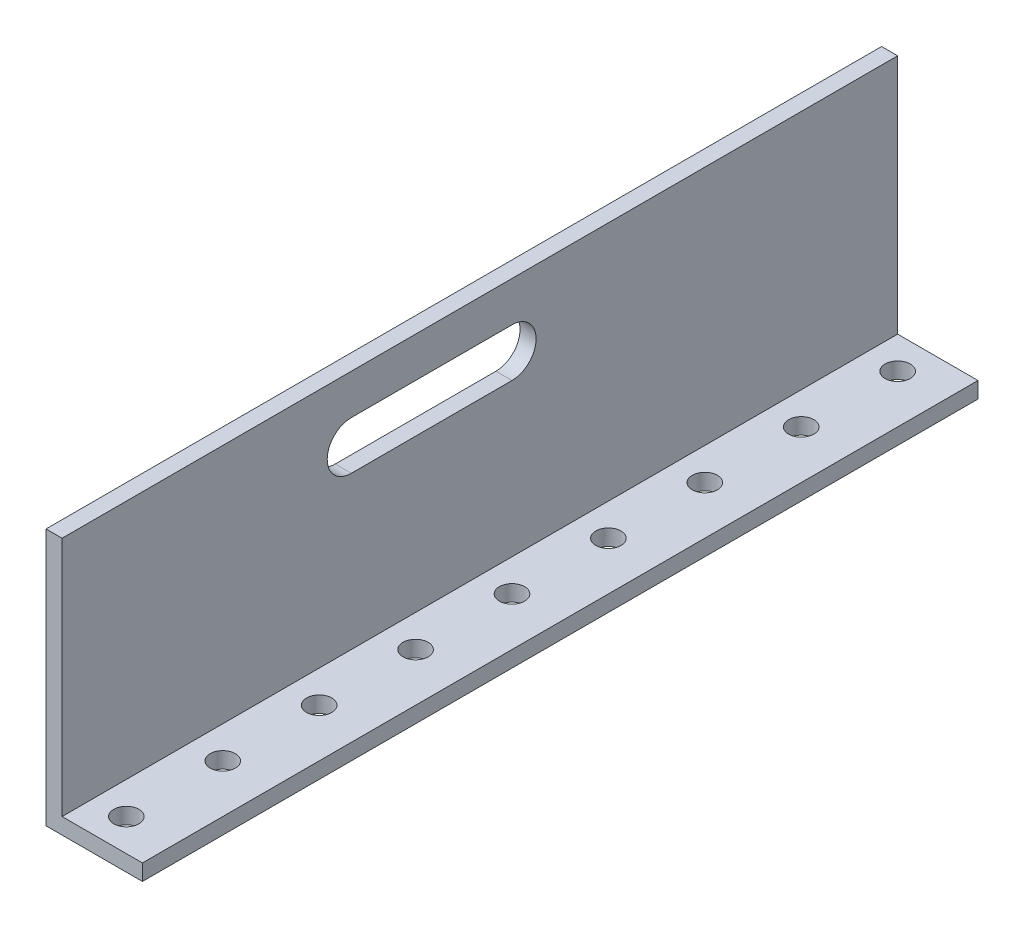
SolidWorks part; units mm, degrees
material "6061-T6 (SS)"
ref_plane "Front Plane" through (0, 0, 0) normal (0, 0, 1) x (1, 0, 0)
ref_plane "Top Plane" through (0, 0, 0) normal (0, 1, 0) x (1, 0, 0)
ref_plane "Right Plane" through (0, 0, 0) normal (1, 0, 0) x (0, 0, -1)
sketch "Sketch1" plane through (0, 0, 0) normal (0, 0, 1) x (1, 0, 0)
  line L1 (0, 0) -> (3.175, 0)
  line L2 (0, 0) -> (0, 50.8)
  line L3 (0, 50.8) -> (3.175, 50.8)
  line L4 (3.175, 0) -> (3.175, 50.8)
  line L5 (0, 0) -> (19.05, 0)
  line L6 (0, 0) -> (0, 3.175)
  line L7 (0, 3.175) -> (19.05, 3.175)
  line L8 (19.05, 0) -> (19.05, 3.175)
  dimension "D1" = 3.175
  dimension "D2" = 3.175
  dimension "D3" = 50.8
  dimension "D4" = 19.05
extrude "Boss-Extrude1" add sketch "Sketch1" along normal blind 165.1 contours L2 L7 L4 L3 | L7 L2 L1 L4 | L5 L8 L7 L4
sketch "Sketch2" plane through (0, 3.175, 0) normal (0, 1, 0) x (1, 0, 0)
  line L0 (3.175, 0) -> (19.05, 0) construction
  line L2 (3.175, -165.1) -> (3.175, 0) construction
  circle A0 centre (9.525, -6.35) radius 2.4892
  circle A1 centre (9.525, -25.4) radius 2.4892
  circle A2 centre (9.525, -44.45) radius 2.4892
  circle A3 centre (9.525, -63.5) radius 2.4892
  circle A4 centre (9.525, -82.55) radius 2.4892
  circle A5 centre (9.525, -101.6) radius 2.4892
  circle A6 centre (9.525, -120.65) radius 2.4892
  circle A7 centre (9.525, -139.7) radius 2.4892
  circle A8 centre (9.525, -158.75) radius 2.4892
  dimension "D1" = 6.35
  dimension "D2" = 4.9784
  dimension "D3" = 6.35
  dimension "D5" = 19.05
  dimension "D4" = 9
extrude "Cut-Extrude1" cut sketch "Sketch2" against normal blind 165.1
sketch "Sketch3" plane through (0, 0, 0) normal (-1, 0, 0) x (0, 0, 1)
  line L0 (76.2, 42.8625) -> (107.95, 42.8625)
  line L1 (107.95, 33.3375) -> (76.2, 33.3375)
  line L2 (165.1, 50.8) -> (0, 50.8) construction
  line L3 (165.1, 0) -> (0, 0) construction
  line L4 (0, 0) -> (0, 50.8) construction
  circle A0 centre (76.2, 38.1) radius 4.7625
  circle A1 centre (107.95, 38.1) radius 4.7625
  point P8 (0, 0)
  point P11 (82.55, 0)
  point P15 (0, 0)
  dimension "D1" = 9.525
  dimension "D2" = 31.75
  dimension "D3" = 12.7
  dimension "D4" = 76.2
extrude "Cut-Extrude2" cut sketch "Sketch3" against normal blind 184.15 contours A1 L0 A0 L1 | A0 | A1
